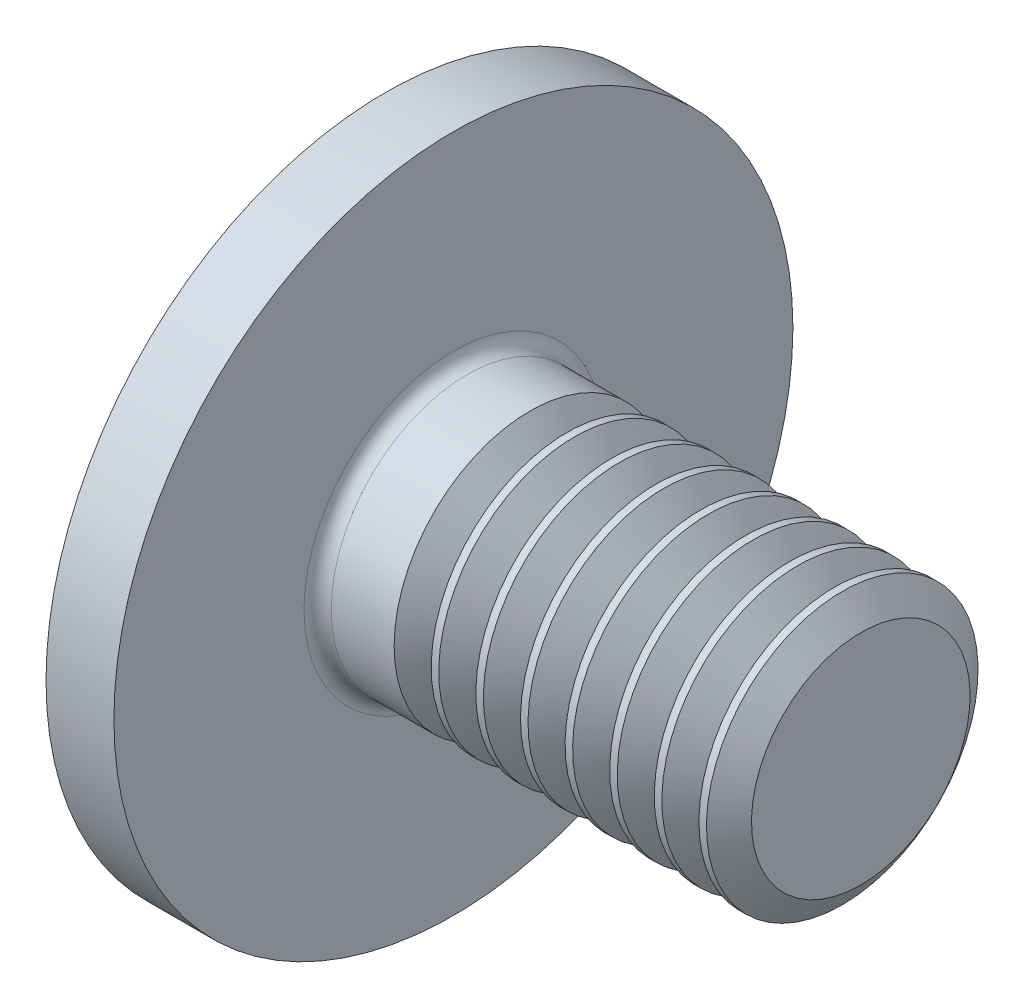
SolidWorks part; units mm, degrees
revolve "Base-Revolve" add sketch "BodySke"
sketch "BodySke" plane through (0, 0, 0) normal (0, 0, 1) x (1, 0, 0)
  line L1 (3.05, 2) -> (3.05, 5)
  line L2 (3.05, 2) -> (9.05, 2)
  line L3 (9.05, 2) -> (9.05, 0)
  line L4 (9.05, 0) -> (2.05, 0)
  line L5 (-6.35, 0) -> (82.55, 0) construction
  line L8 (3.05, 5) -> (2.05, 5)
  line L10 (3.75, 3.5875) -> (3.75, -5.9375) construction
  line L11 (4.45, 4.35) -> (4.45, -5.175) construction
  line L12 (2.05, 5) -> (2.05, 0)
  dimension "Advance" = 0.7
  dimension "Thread_nom" = 4.6
  dimension "HTc" = 1
  dimension "Head_ht" = 3.05
  dimension "Head_dia" = 10
  dimension "Length" = 6
  dimension "Diameter" = 4
cosmetic thread "ThreadCosmetic" [suppressed]
revolve "ThreadSchematic" cut sketch "ThdSchSke" angle 360 about L3
sketch "ThdSchSke" plane through (0, 0, 0) normal (0, 0, 1) x (1, 0, 0)
  line L0 (4.45, -1.61) -> (4.1769, -2)
  line L1 (4.45, -1.61) -> (4.7231, -2)
  line L2 (4.7231, -2) -> (4.7231, -2.5)
  line L3 (-3.175, 0) -> (5.1513, 0) construction
  line L4 (3.05, -5) -> (3.05, 5) construction
  line L5 (4.7231, -2.5) -> (4.1769, -2.5)
  line L6 (4.1769, -2.5) -> (4.1769, -2)
  dimension "Diameter" = 4
  dimension "Thread_minor" = 3.22
  dimension "Start" = 1.4
fillet "Fillet1" radius 0.2 1 edges at (3.05, 0, 2)
ref_plane "Plane1" through (0, 0, 0) normal (0, 0, 1) x (1, 0, 0)
ref_plane "Plane2" through (0, 0, 0) normal (0, 1, 0) x (1, 0, 0)
ref_plane "Plane3" through (0, 0, 0) normal (1, 0, 0) x (0, 0, -1)
sketch "Sketch3" plane through (0, 0, 0) normal (1, 0, 0) x (0, 0, -1)
  line L0 (-0.515, 2.15) -> (0.515, 2.15)
  line L1 (0.515, 2.15) -> (0.515, -2.15)
  line L2 (0.515, -2.15) -> (-0.515, -2.15)
  line L3 (-0.515, -2.15) -> (-0.515, 2.15)
  dimension "Cross_dia" = 4.3
  dimension "Cross_width" = 1.03
  dimension "D1" = 2.15
  dimension "D2" = 0.515
ref_plane "Plane4" through (2.34, 0, 0) normal (1, 0, 0) x (0, 0, -1)
sketch "PanSke" plane through (0, 0, 0) normal (0, 0, 1) x (1, 0, 0)
  line L0 (0, 0) -> (15.875, 0) construction
  line L1 (-6.35, 0) -> (82.55, 0) construction
  line L2 (2.05, 5) -> (2.05, -5) construction
  line L4 (2.05, 4.4246) -> (2.05, 0)
  line L5 (0, 0) -> (2.05, 0)
  arc A0 (0, 0) -> (2.05, 4.4246) centre (5.8, 0) cw
  dimension "RADf" = 5.8
revolve "Pan" add sketch "PanSke" angle 360 about L0
sketch "Sketch4" plane through (2.34, 0, 0) normal (1, 0, 0) x (0, 0, -1)
  line L0 (-0.515, 2.1065) -> (0.515, 2.1065)
  line L3 (0.515, 2.1065) -> (0.515, -2.1065)
  line L4 (0.515, -2.1065) -> (-0.515, -2.1065)
  line L5 (-0.515, -2.1065) -> (-0.515, 2.1065)
  dimension "D2" = 4.213
  dimension "D1" = 1.03
  dimension "D4" = 2.1065
  dimension "D3" = 0.515
loft "Recess" cut profiles "Sketch3", "Sketch4"
pattern_circular "RecPat" count 2 every 90 about axis through (0, 0, 0) along (1, 0, 0) of "Recess"
sketch "RecCorSke" plane through (0, 0, 0) normal (0, 0, 1) x (1, 0, 0)
  line L0 (-3.175, 0) -> (15.875, 0) construction
  line L2 (0, 0) -> (0, 1.1727)
  line L3 (0, 1.1727) -> (4.6, 0.851)
  line L4 (4.6, 0.851) -> (4.8765, 0)
  line L5 (4.8765, 0) -> (0, 0)
  dimension "Diameter" = 1.702
  dimension "Depth" = 4.6
  dimension "Draft_angle" = 4
  dimension "Bottom_angle" = 18
revolve "RecessCore" cut sketch "RecCorSke" angle 360 about L0
pattern_linear "ThdSchPat" count 8 spacing 0.6571 along (1, 0, 0) of "ThreadSchematic"
equation "\"D1@Sketch3\" = \"Cross_dia@Sketch3\" / 2"
equation "\"D2@Sketch3\" = \"Cross_width@Sketch3\" / 2"
equation "\"D1@Sketch4\" = \"Cross_width@Sketch3\""
equation "\"D3@Sketch4\" = \"D1@Sketch4\" / 2"
equation "\"D4@Sketch4\" = \"D2@Sketch4\" / 2"
equation "\"Thread_length@ThreadCosmetic\" = ((sgn( (\"Length@BodySke\" - \"Advance@BodySke\" * 2.0 ) - \"Thread_nom@BodySke\" )-1)*( (\"Length@BodySke\" - \"Advance@BodySke\" * 2.0 ) - \"Thread_nom@BodySke\" ))/-2+ \"Thread_nom@BodySke\""
equation "\"Thread_minor@ThdSchSke\" = \"Thread_minor@ThreadCosmetic\""
equation "\"Diameter@ThdSchSke\" = \"Diameter@BodySke\""
equation "\"Overcut@ThdSchSke\" = \"Diameter@BodySke\" * 1.25"
equation "\"Start@ThdSchSke\" =  \"Length@BodySke\" -  \"Thread_length@ThreadCosmetic\"  '---Non-countersunk---"
equation "\"Num_threads@ThdSchPat\" = int( \"Thread_length@ThreadCosmetic\" / \"Advance@BodySke\" + 0.999 )  + 1"
equation "\"Advance@ThdSchPat\" = \"Thread_length@ThreadCosmetic\" /  (\"Num_threads@ThdSchPat\" - 1) 'relax it"
